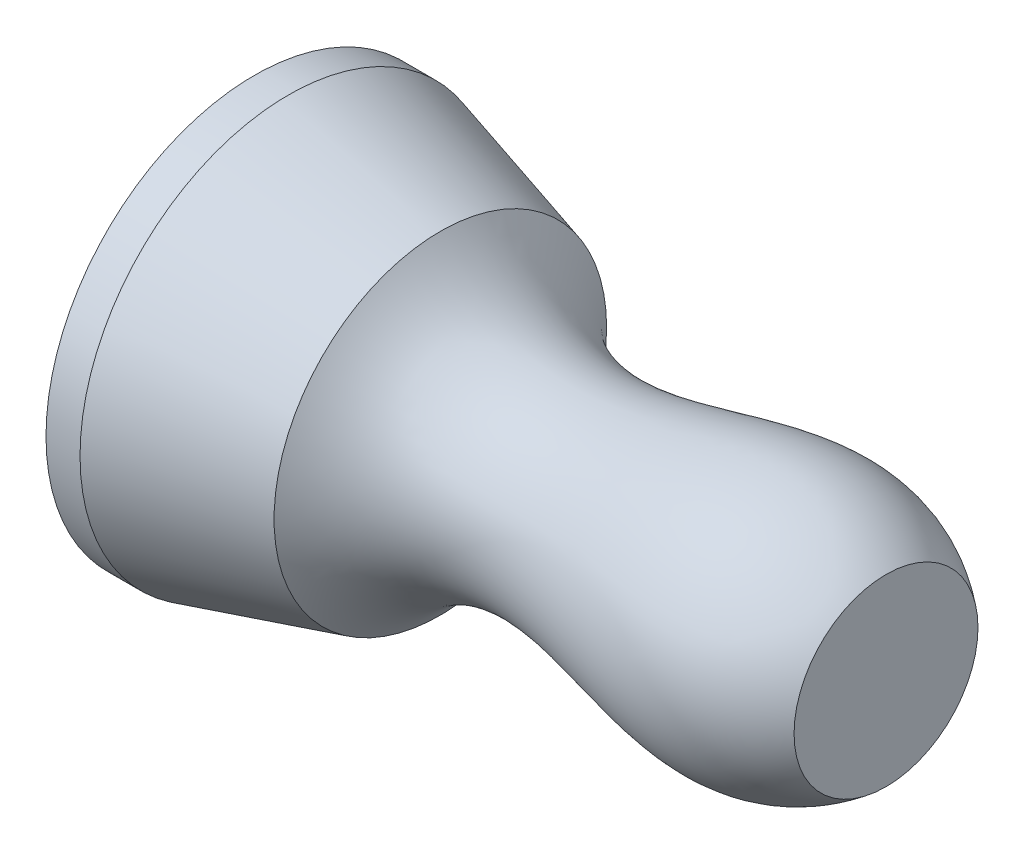
SolidWorks part; units mm, degrees
ref_plane "前基準面" through (0, 0, 0) normal (0, 0, 1) x (1, 0, 0)
ref_plane "上基準面" through (0, 0, 0) normal (0, 1, 0) x (1, 0, 0)
ref_plane "右基準面" through (0, 0, 0) normal (1, 0, 0) x (0, 0, -1)
sketch "草圖2" plane through (0, 0, 0) normal (0, 1, 0) x (1, 0, 0)
  line L0 (0, 0) -> (0, 19.0083)
  line L1 (0, 19.0083) -> (3.1034, 19.0083)
  line L2 (3.1034, 19.0083) -> (16.9493, 15.1606)
  line L3 (57.5905, 8.3858) -> (57.5905, 0)
  line L4 (57.5905, 0) -> (0, 0)
  spline S0 degree 3 poles (16.9493, 15.1606) (29.0361, -0.3656) (43.8738, 19.1512) (57.5905, 8.3858) knots 0 0 0 0 1 1 1 1
  point P6 (16.9493, 15.1606)
revolve "旋轉1" add sketch "草圖2" angle 360 about L4
